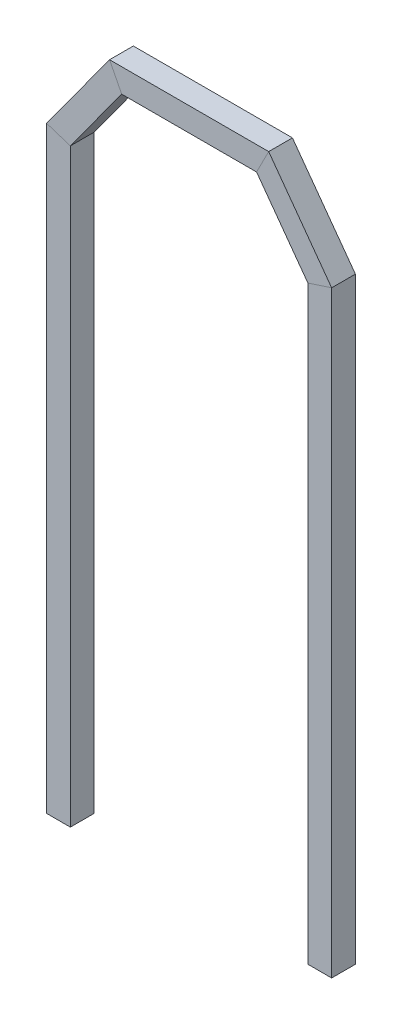
SolidWorks part; units mm, degrees
material "PVC Rigid"
ref_plane "Front Plane" through (0, 0, 0) normal (0, 0, 1) x (1, 0, 0)
ref_plane "Top Plane" through (0, 0, 0) normal (0, 1, 0) x (1, 0, 0)
ref_plane "Right Plane" through (0, 0, 0) normal (1, 0, 0) x (0, 0, -1)
sketch "Sketch1" plane through (0, 0, 0) normal (0, 0, 1) x (1, 0, 0)
  line L0 (330, 0) -> (330, 1500)
  line L1 (330, 1500) -> (185.6711, 1698.2834)
  line L2 (185.6711, 1698.2834) -> (0, 1698.2834)
  point P2 (0, 0)
  dimension "D1" = 330
  dimension "D2" = 1500
sketch "Sketch2" plane through (0, 0, 0) normal (0, 1, 0) x (1, 0, 0)
  line L0 (305, -25) -> (305, 25)
  line L1 (300, -30) -> (360, -30)
  line L2 (300, -30) -> (300, 30)
  line L3 (300, 30) -> (360, 30)
  line L4 (360, -30) -> (360, 30)
  line L5 (300, -30) -> (360, 30) construction
  line L6 (300, 30) -> (360, -30) construction
  line L7 (305, 25) -> (355, 25)
  line L8 (355, -25) -> (355, 25)
  line L9 (305, -25) -> (355, -25)
  point P0 (330, 0)
  dimension "D1" = 60
  dimension "D2" = 60
  dimension "D3" = 5
sweep "Sweep1" add profiles "Sketch2" path "Sketch1"
mirror "Mirror1" about plane through (0, 0, 0) normal (1, 0, 0) of "Sweep1"
